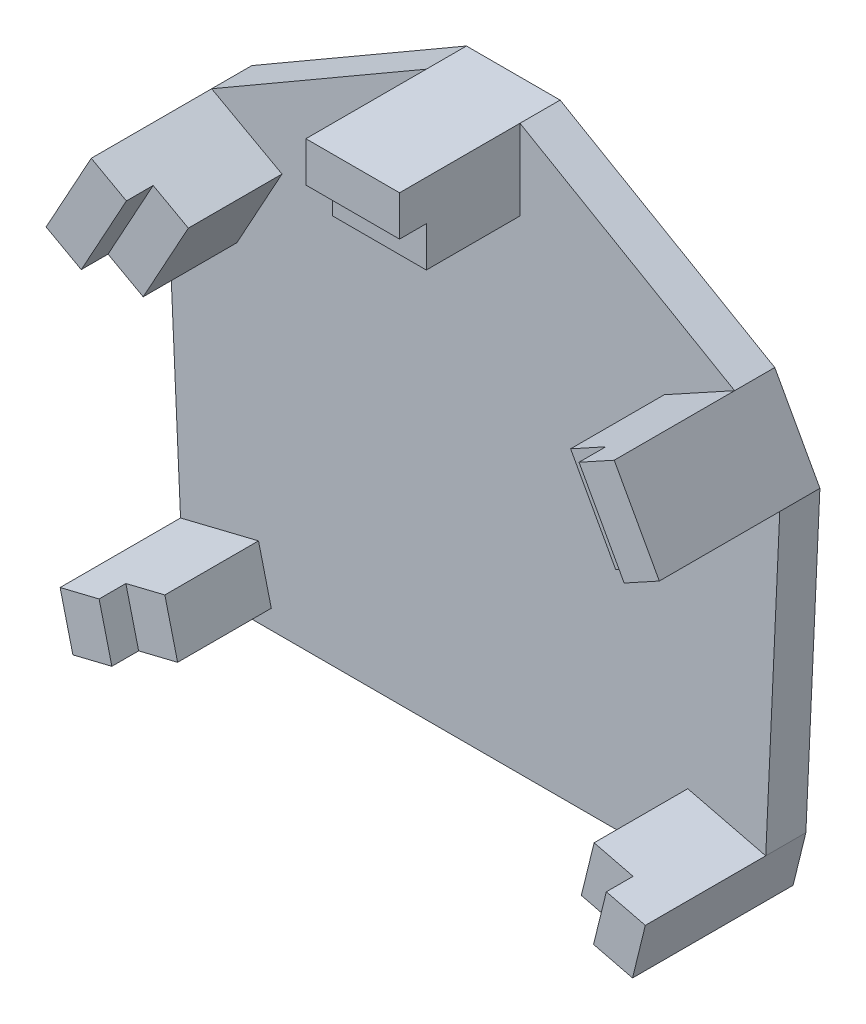
SolidWorks part; units mm, degrees
ref_plane "Front Plane" through (0, 0, 0) normal (0, 0, 1) x (1, 0, 0)
ref_plane "Top Plane" through (0, 0, 0) normal (0, 1, 0) x (1, 0, 0)
ref_plane "Right Plane" through (0, 0, 0) normal (1, 0, 0) x (0, 0, -1)
sketch "Sketch1" plane through (0, 0, 0) normal (0, 0, 1) x (1, 0, 0)
  line L0 (18, -11.4) -> (-18, -11.4)
  line L1 (-18, -11.4) -> (-20.8, 0)
  line L2 (-20.8, 0) -> (-20.8, 2.1)
  line L3 (-20.8, 2.1) -> (-15.6, 2.1)
  line L4 (-15.6, 2.1) -> (-15.6, 9.9)
  line L5 (-15.6, 9.9) -> (-20.8, 9.9)
  line L6 (-20.8, 9.9) -> (-20.8, 12.2)
  line L7 (-20.8, 12.2) -> (-16.4, 20.2)
  line L8 (-16.4, 20.2) -> (-6, 27)
  line L9 (-6, 27) -> (6, 27)
  line L10 (6, 27) -> (16.4, 20.2)
  line L11 (16.4, 20.2) -> (20.8, 12.2)
  line L12 (20.8, 12.2) -> (20.8, 0)
  line L13 (20.8, 0) -> (18, -11.4)
  line L14 (0, 0) -> (0, -11.4) construction
  line L15 (0, 0) -> (0, 27) construction
  line L16 (-16.4, 20.2) -> (16.4, 20.2) construction
  line L17 (-20.8, 12.2) -> (20.8, 12.2) construction
  line L18 (-20.8, 0) -> (20.8, 0) construction
  point P17 (18, 12.6157)
  point P19 (18, -13.8772)
  point P20 (0, 0)
  point P21 (16.8609, 18.7409)
  point P22 (14.9553, 21.1553)
  point P23 (16.3792, 22.5792)
  point P24 (16.8933, 23.0933)
  point P25 (18.5633, 21.0278)
  point P26 (18, 20.2)
  point P27 (0, 0)
  point P28 (17.8368, 20.5932)
  point P29 (31.0616, 22.4517)
  dimension "D1" = 36
  dimension "D2" = 12.2
  dimension "D3" = 2.1
  dimension "D4" = 12
  dimension "D5" = 11.4
  dimension "D6" = 38.4
  dimension "D7" = 8
  dimension "D8" = 2.3
  dimension "D9" = 5.2
  dimension "D10" = 41.6
  dimension "D11" = 32.8
sketch "Sketch2" plane through (0, 0, 0) normal (0, 0, 1) x (1, 0, 0)
  line L0 (-6, 27) -> (6, 27) construction
  line L1 (-3.5, 27) -> (3.5, 27)
  line L2 (-3.5, 27) -> (-3.5, 30)
  line L3 (-3.5, 30) -> (3.5, 30)
  line L4 (3.5, 27) -> (3.5, 30)
  line L5 (-18.9541, -7.5155) -> (-18, -11.4)
  line L6 (-18.9541, -7.5155) -> (-21.8675, -8.231)
  line L7 (-18, -11.4) -> (-20.9134, -12.1156)
  line L8 (-21.8675, -8.231) -> (-20.9134, -12.1156)
  line L9 (-18, -11.4) -> (-20.8, 0) construction
  line L10 (-20.2867, 13.1332) -> (-16.9133, 19.2668)
  line L11 (-20.2867, 13.1332) -> (-22.9154, 14.579)
  line L12 (-16.9133, 19.2668) -> (-19.5419, 20.7125)
  line L13 (-22.9154, 14.579) -> (-19.5419, 20.7125)
  line L14 (-20.8, 12.2) -> (-16.4, 20.2) construction
  line L15 (0, 0) -> (0, 16.2) construction
  line L16 (-20.8, 0) -> (20.8, 0) construction
  line L17 (0, 0) -> (0, 27) construction
  line L18 (22.9154, 14.579) -> (19.5419, 20.7125)
  line L19 (16.9133, 19.2668) -> (19.5419, 20.7125)
  line L20 (20.2867, 13.1332) -> (22.9154, 14.579)
  line L21 (20.2867, 13.1332) -> (16.9133, 19.2668)
  line L22 (21.8675, -8.231) -> (20.9134, -12.1156)
  line L23 (18, -11.4) -> (20.9134, -12.1156)
  line L24 (18.9541, -7.5155) -> (21.8675, -8.231)
  line L25 (18.9541, -7.5155) -> (18, -11.4)
  point P24 (-18.6, 16.2)
  point P26 (0, 0)
  point P35 (-18, -11.4)
  point P36 (18.6, 16.2)
  point P37 (0, 0)
  point P39 (-21.6546, -9.0979)
  dimension "D1" = 7
  dimension "D2" = 3
  dimension "D3" = 4
extrude "Boss-Extrude1" add sketch "Sketch2" along normal blind 2
sketch "Sketch3" plane through (0, 0, 0) normal (0, 0, 1) x (1, 0, 0)
  line L0 (20.9134, -12.1156) -> (21.8675, -8.231)
  line L1 (20.9134, -12.1156) -> (15.0866, -10.6844)
  line L2 (21.8675, -8.231) -> (16.0407, -6.7999)
  line L3 (15.0866, -10.6844) -> (16.0407, -6.7999)
  line L4 (22.9154, 14.579) -> (19.5419, 20.7125)
  line L5 (22.9154, 14.579) -> (17.6581, 11.6875)
  line L6 (19.5419, 20.7125) -> (14.2846, 17.821)
  line L7 (17.6581, 11.6875) -> (14.2846, 17.821)
  line L8 (3.5, 30) -> (-3.5, 30)
  line L9 (3.5, 30) -> (3.5, 24)
  line L10 (-3.5, 30) -> (-3.5, 24)
  line L11 (3.5, 24) -> (-3.5, 24)
  line L13 (0, 0) -> (0, 17.0435) construction
  line L14 (-20.8, 0) -> (20.8, 0) construction
  line L15 (0, 0) -> (0, 27) construction
  line L16 (-17.6581, 11.6875) -> (-14.2846, 17.821)
  line L17 (-19.5419, 20.7125) -> (-14.2846, 17.821)
  line L18 (-22.9154, 14.579) -> (-17.6581, 11.6875)
  line L19 (-22.9154, 14.579) -> (-19.5419, 20.7125)
  line L20 (-15.0866, -10.6844) -> (-16.0407, -6.7999)
  line L21 (-21.8675, -8.231) -> (-16.0407, -6.7999)
  line L22 (-20.9134, -12.1156) -> (-15.0866, -10.6844)
  line L23 (-20.9134, -12.1156) -> (-21.8675, -8.231)
  dimension "D1" = 6
extrude "Boss-Extrude2" add sketch "Sketch3" against normal blind 7
sketch "Sketch4" plane through (0, 0, -7) normal (0, 0, -1) x (-1, 0, 0)
  line L0 (-21.8675, -8.231) -> (-22.9154, 14.579)
  line L1 (-22.9154, 14.579) -> (-19.5419, 20.7125)
  line L2 (-19.5419, 20.7125) -> (-3.5, 30)
  line L3 (-3.5, 30) -> (3.5, 30)
  line L4 (3.5, 30) -> (19.5419, 20.7125)
  line L5 (19.5419, 20.7125) -> (22.9154, 14.579)
  line L6 (22.9154, 14.579) -> (21.8675, -8.231)
  line L7 (21.8675, -8.231) -> (20.9134, -12.1156)
  line L8 (20.9134, -12.1156) -> (-20.9134, -12.1156)
  line L9 (-20.9134, -12.1156) -> (-21.8675, -8.231)
extrude "Boss-Extrude3" add sketch "Sketch4" along normal blind 3
